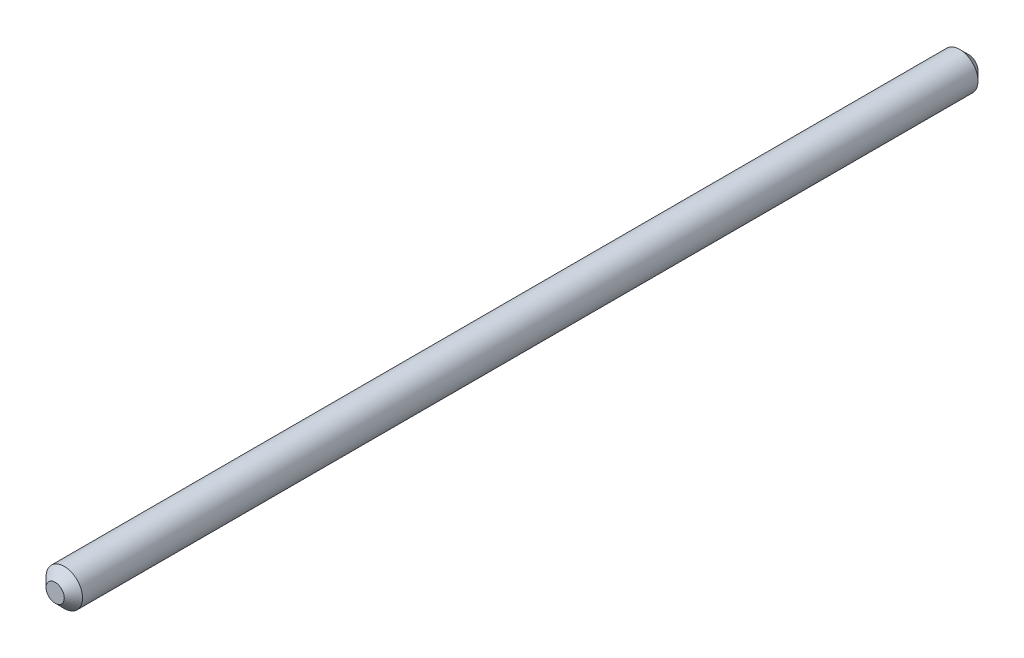
SolidWorks part; units mm, degrees
ref_plane "Front Plane" through (0, 0, 0) normal (0, 0, 1) x (1, 0, 0)
ref_plane "Top Plane" through (0, 0, 0) normal (0, 1, 0) x (1, 0, 0)
ref_plane "Right Plane" through (0, 0, 0) normal (1, 0, 0) x (0, 0, -1)
sketch "Sketch1" plane through (0, 0, 0) normal (0, 0, 1) x (1, 0, 0)
  circle A0 centre (0, 0) radius 1
  dimension "D1" = 2
extrude "Boss-Extrude1" add sketch "Sketch1" along normal blind 50
chamfer "Chamfer1" distance 0.5 angle 45 2 edges at (1, 0, 0) (1, 0, 50)
